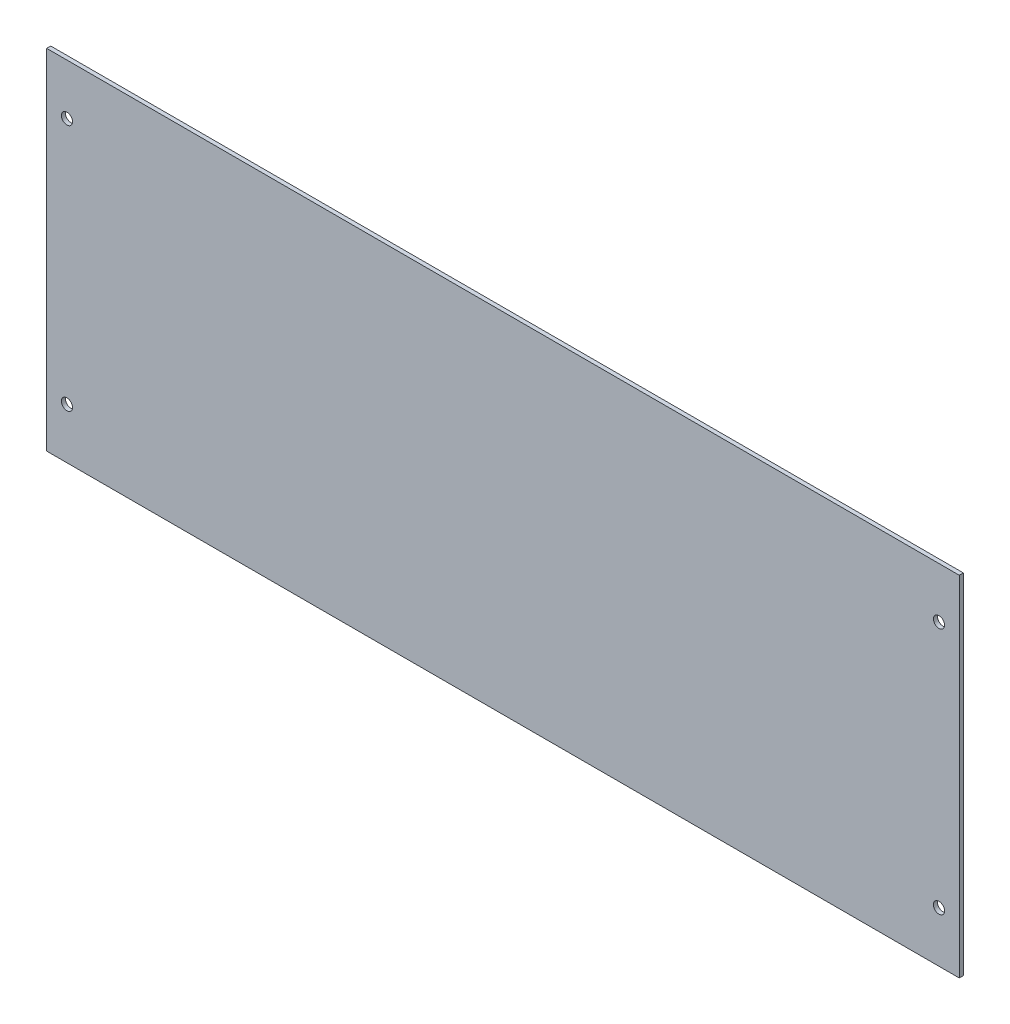
SolidWorks part; units mm, degrees
material "1345 Alloy"
ref_plane "Front Plane" through (0, 0, 0) normal (0, 0, 1) x (1, 0, 0)
ref_plane "Top Plane" through (0, 0, 0) normal (0, 1, 0) x (1, 0, 0)
ref_plane "Right Plane" through (0, 0, 0) normal (1, 0, 0) x (0, 0, -1)
sketch "Sketch1" plane through (0, 0, 0) normal (0, 0, 1) x (1, 0, 0)
  line L1 (-225, 86) -> (225, 86)
  line L2 (-225, 86) -> (-225, -86)
  line L3 (-225, -86) -> (225, -86)
  line L4 (225, 86) -> (225, -86)
  line L5 (-225, 86) -> (225, -86) construction
  line L6 (-225, -86) -> (225, 86) construction
  point P0 (0, 0)
  dimension "D1" = 450
  dimension "D2" = 172
extrude "Boss-Extrude1" add sketch "Sketch1" along normal blind 2
sketch "Sketch2" plane through (0, 0, 2) normal (0, 0, 1) x (1, 0, 0)
  line L5 (215, -61) -> (-215, 61) construction
  line L6 (215, 61) -> (-215, -61) construction
  circle A0 centre (-215, 61) radius 2.75
  circle A1 centre (215, 61) radius 2.75
  circle A2 centre (215, -61) radius 2.75
  circle A3 centre (-215, -61) radius 2.75
  point P0 (0, 0)
  dimension "D3" = 5.5
  dimension "D1" = 430
  dimension "D2" = 122
  dimension "D4" = 2
  dimension "D5" = 2
extrude "Cut-Extrude1" cut sketch "Sketch2" against normal through all
